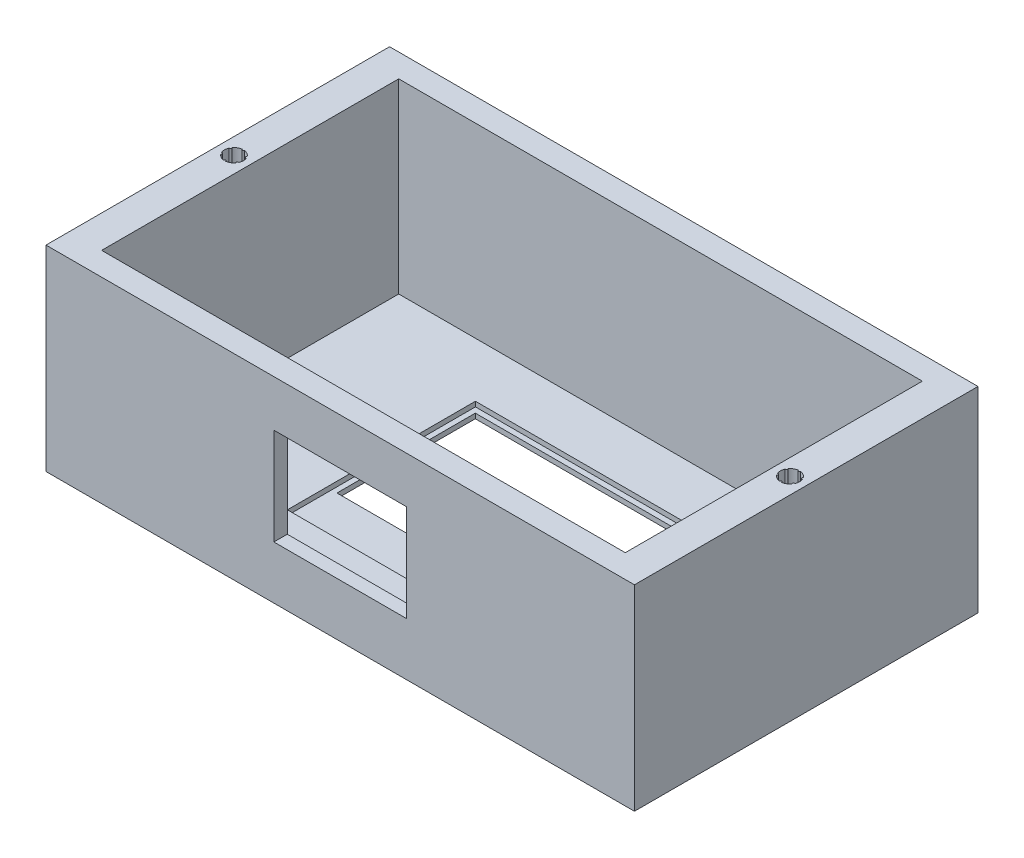
SolidWorks part; units mm, degrees
ref_plane "Front Plane" through (0, 0, 0) normal (0, 0, 1) x (1, 0, 0)
ref_plane "Top Plane" through (0, 0, 0) normal (0, 1, 0) x (1, 0, 0)
ref_plane "Right Plane" through (0, 0, 0) normal (1, 0, 0) x (0, 0, -1)
sketch "Sketch1" plane through (0, 0, 0) normal (0, 1, 0) x (1, 0, 0)
  line L1 (30.0002, -17.5157) -> (-30.0002, -17.5157)
  line L2 (30.0002, -17.5157) -> (30.0002, 17.5157)
  line L3 (30.0002, 17.5157) -> (-30.0002, 17.5157)
  line L4 (-30.0002, -17.5157) -> (-30.0002, 17.5157)
  line L5 (30.0002, -17.5157) -> (-30.0002, 17.5157) construction
  line L6 (30.0002, 17.5157) -> (-30.0002, -17.5157) construction
  point P0 (0, 0)
extrude "Boss-Extrude1" add sketch "Sketch1" along normal blind 20
sketch "Sketch2" plane through (0, 20, 0) normal (0, 1, 0) x (1, 0, 0)
  line L0 (0, 0) -> (-30.0002, 0) construction
  line L1 (-30.0002, 17.5157) -> (-30.0002, -17.5157) construction
  line L3 (26.6966, -15.1464) -> (-26.6966, -15.1464)
  line L4 (26.6966, -15.1464) -> (26.6966, 15.1464)
  line L5 (26.6966, 15.1464) -> (-26.6966, 15.1464)
  line L6 (-26.6966, -15.1464) -> (-26.6966, 15.1464)
  line L7 (26.6966, -15.1464) -> (-26.6966, 15.1464) construction
  line L8 (26.6966, 15.1464) -> (-26.6966, -15.1464) construction
extrude "Cut-Extrude1" cut sketch "Sketch2" against normal blind 19
sketch "Sketch3" plane through (0, 1, 0) normal (0, 1, 0) x (1, 0, 0)
  line L1 (13.3162, -9.5869) -> (-13.3162, -9.5869)
  line L2 (13.3162, -9.5869) -> (13.3162, 9.5869)
  line L3 (13.3162, 9.5869) -> (-13.3162, 9.5869)
  line L4 (-13.3162, -9.5869) -> (-13.3162, 9.5869)
  line L5 (13.3162, -9.5869) -> (-13.3162, 9.5869) construction
  line L6 (13.3162, 9.5869) -> (-13.3162, -9.5869) construction
  point P0 (0, 0)
extrude "Cut-Extrude2" cut sketch "Sketch3" against normal blind 0.5
sketch "Sketch4" plane through (0, 0.5, 0) normal (0, 1, 0) x (1, 0, 0)
  line L0 (0, -9.5869) -> (0, -5.0772) construction
  line L1 (-13.3162, -9.5869) -> (13.3162, -9.5869) construction
  line L2 (0, -5.0772) -> (-13.3162, -5.0772) construction
  line L3 (-13.3162, 9.5869) -> (-13.3162, -9.5869) construction
  line L4 (0, -5.0772) -> (13.3162, -5.0772) construction
  line L5 (13.3162, -9.5869) -> (13.3162, 9.5869) construction
  line L6 (0, -5.0772) -> (0, 9.0324) construction
  line L7 (0, -5.0772) -> (-12.7727, -5.0772)
  line L8 (0, -5.0772) -> (12.7651, -5.0772)
  line L9 (0, 9.0324) -> (-12.7727, 9.0324)
  line L10 (-12.7727, 9.0324) -> (-12.7727, -5.0772)
  line L11 (0, 9.0324) -> (12.7651, 9.0324)
  line L12 (12.7651, 9.0324) -> (12.7651, -5.0772)
extrude "Cut-Extrude3" cut sketch "Sketch4" against normal blind 0.5
sketch "Sketch7" plane through (0, 20, 0) normal (0, 1, 0) x (1, 0, 0)
  line L0 (-30.0002, 0) -> (-26.6966, 0) construction
  line L1 (-30.0002, 17.5157) -> (-30.0002, -17.5157) construction
  line L2 (-26.6966, 15.1464) -> (-26.6966, -15.1464) construction
  line L3 (30.0002, 0) -> (26.6966, 0) construction
  line L4 (30.0002, -17.5157) -> (30.0002, 17.5157) construction
  line L5 (26.6966, -15.1464) -> (26.6966, 15.1464) construction
  circle A0 centre (28.3484, 0) radius 0.9691
  circle A1 centre (-28.3484, 0) radius 0.9614
extrude "Cut-Extrude6" cut sketch "Sketch7" against normal blind 5
sketch "Sketch8" plane through (0, 20, 0) normal (0, 1, 0) x (1, 0, 0)
  line L0 (30.0002, 0) -> (28.3484, 0) construction
  line L1 (30.0002, -17.5157) -> (30.0002, 17.5157) construction
  line L2 (-30.0002, 0) -> (-28.3484, 0) construction
  line L3 (-30.0002, 17.5157) -> (-30.0002, -17.5157) construction
  line L4 (0, -11) -> (0, 11) construction
  circle A0 centre (-28.3484, 0.9614) radius 0.1046
  circle A1 centre (-28.3484, 0) radius 0.9614 construction
  circle A2 centre (-28.3484, 0) radius 0.9614 construction
  circle A3 centre (-27.5159, 0.4807) radius 0.1046
  circle A4 centre (-27.5159, -0.4807) radius 0.1046
  circle A5 centre (-28.3484, -0.9614) radius 0.1046
  circle A6 centre (-29.181, -0.4807) radius 0.1046
  circle A7 centre (-29.181, 0.4807) radius 0.1046
  circle A8 centre (27.5159, 0.4807) radius 0.1046
  circle A9 centre (27.5159, -0.4807) radius 0.1046
  circle A10 centre (28.3484, -0.9614) radius 0.1046
  circle A11 centre (29.181, -0.4807) radius 0.1046
  circle A12 centre (29.181, 0.4807) radius 0.1046
  circle A13 centre (28.3484, 0.9614) radius 0.1046
  dimension "D1" = 6
extrude "Boss-Extrude2" add sketch "Sketch8" against normal blind 4
sketch "Sketch9" plane through (0, 0, 0) normal (0, -1, 0) x (1, 0, 0)
  line L0 (-30.0002, 0) -> (-12.7727, 0) construction
  line L1 (-30.0002, -17.5157) -> (-30.0002, 17.5157) construction
  line L2 (-12.7727, -9.0324) -> (-12.7727, 5.0772) construction
  circle A0 centre (-21.3865, 0) radius 0.7998
extrude "Cut-Extrude7" cut sketch "Sketch9" against normal blind 6
sketch "Sketch10" plane through (0, 1, 0) normal (0, 1, 0) x (1, 0, 0)
  circle A0 centre (-21.3865, 0) radius 1.2918
extrude "Cut-Extrude8" cut sketch "Sketch10" against normal blind 0.5
sketch "Sketch13" plane through (0, 0, 17.5157) normal (0, 0, 1) x (1, 0, 0)
  line L1 (6.7656, 5.3982) -> (-6.7656, 5.3982)
  line L2 (6.7656, 5.3982) -> (6.7656, 15.2723)
  line L3 (6.7656, 15.2723) -> (-6.7656, 15.2723)
  line L4 (-6.7656, 5.3982) -> (-6.7656, 15.2723)
  line L5 (6.7656, 5.3982) -> (-6.7656, 15.2723) construction
  line L6 (6.7656, 15.2723) -> (-6.7656, 5.3982) construction
  point P0 (0, 10.3352)
extrude "Cut-Extrude11" cut sketch "Sketch13" against normal blind 10
sketch "Sketch14" plane through (0, 0, 15.1464) normal (0, 0, -1) x (-1, 0, 0)
  line L0 (-6.7656, 5.3982) -> (6.7656, 15.2723) construction
  line L2 (10.2497, 2.8339) -> (-10.2497, 2.8339)
  line L3 (10.2497, 2.8339) -> (10.2497, 17.8366)
  line L4 (10.2497, 17.8366) -> (-10.2497, 17.8366)
  line L5 (-10.2497, 2.8339) -> (-10.2497, 17.8366)
  line L6 (10.2497, 2.8339) -> (-10.2497, 17.8366) construction
  line L7 (10.2497, 17.8366) -> (-10.2497, 2.8339) construction
  point P4 (0, 10.3352)
extrude "Cut-Extrude12" cut sketch "Sketch14" against normal blind 1
